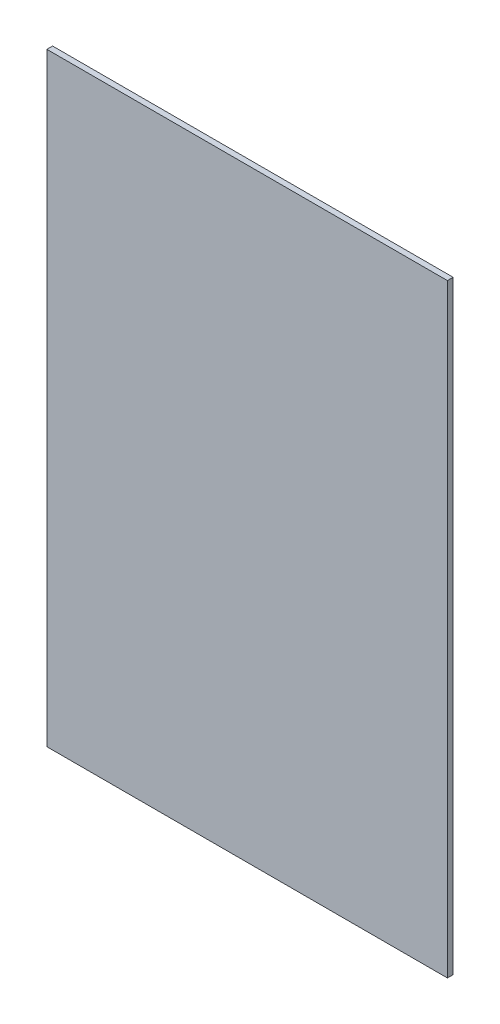
SolidWorks part; units mm, degrees
ref_plane "Front Plane" through (0, 0, 0) normal (0, 0, 1) x (1, 0, 0)
ref_plane "Top Plane" through (0, 0, 0) normal (0, 1, 0) x (1, 0, 0)
ref_plane "Right Plane" through (0, 0, 0) normal (1, 0, 0) x (0, 0, -1)
sketch "Sketch1" plane through (0, 0, 0) normal (0, 0, 1) x (1, 0, 0)
  line L1 (-350, 527.7) -> (350, 527.7)
  line L2 (-350, 527.7) -> (-350, -527.7)
  line L3 (-350, -527.7) -> (350, -527.7)
  line L4 (350, 527.7) -> (350, -527.7)
  line L5 (-350, 527.7) -> (350, -527.7) construction
  line L6 (-350, -527.7) -> (350, 527.7) construction
  point P0 (0, 0)
  dimension "D1" = 1055.4
  dimension "D2" = 700
extrude "Boss-Extrude1" add sketch "Sketch1" along normal blind 10
